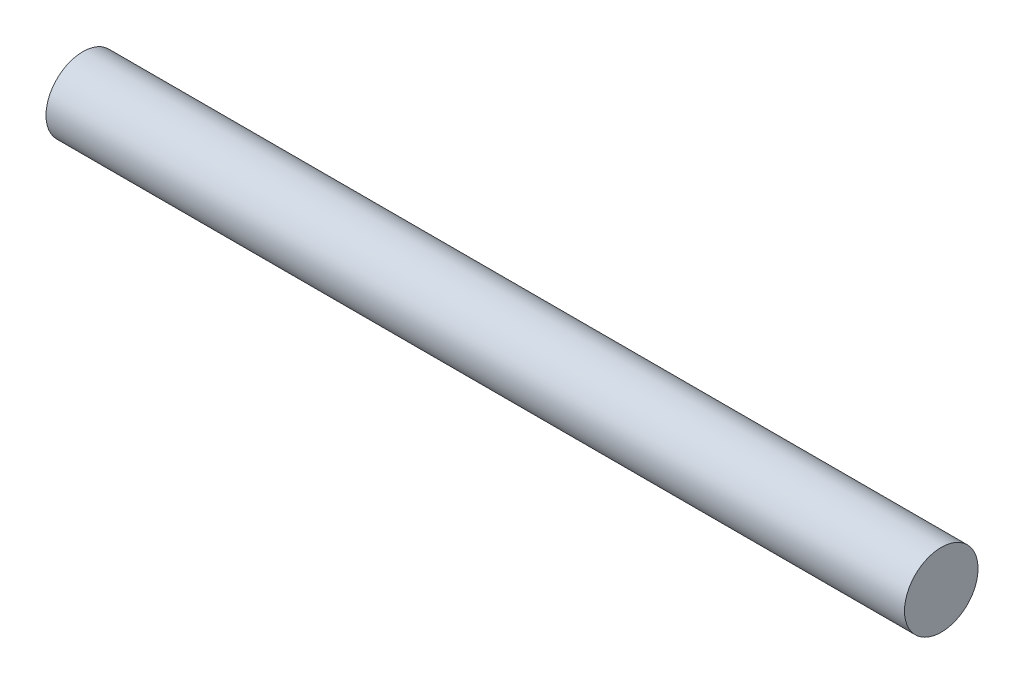
SolidWorks part; units mm, degrees
material "1.0503 (C45)"
ref_plane "Plan de face" through (0, 0, 0) normal (0, 0, 1) x (1, 0, 0)
ref_plane "Plan de dessus" through (0, 0, 0) normal (0, 1, 0) x (1, 0, 0)
ref_plane "Plan de droite" through (0, 0, 0) normal (1, 0, 0) x (0, 0, -1)
sketch "Esquisse1" plane through (0, 0, 0) normal (0, 1, 0) x (1, 0, 0)
  line L0 (-70, 0) -> (70, 0) construction
  line L2 (-70, 0) -> (70, 0)
  line L3 (-70, 0) -> (-70, 6)
  line L4 (-70, 6) -> (70, 6)
  line L5 (70, 0) -> (70, 6)
  dimension "D1" = 12
  dimension "D2" = 140
revolve "Révolution1" add sketch "Esquisse1" angle 360 about L0
